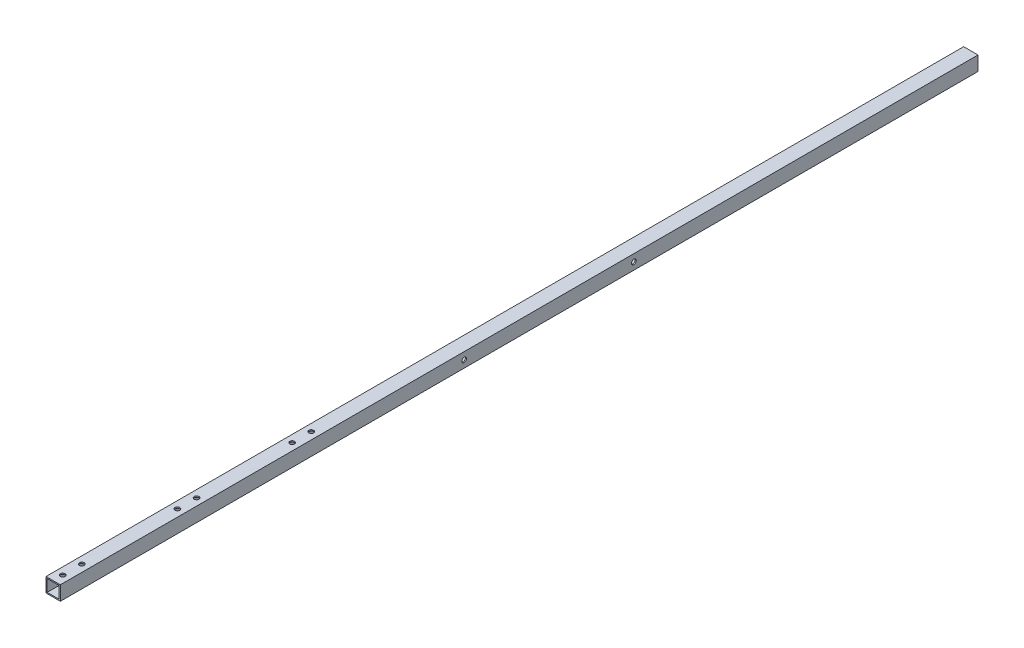
SolidWorks part; units mm, degrees
material "6061 Alloy"
ref_plane "Front Plane" through (0, 0, 0) normal (0, 0, 1) x (1, 0, 0)
ref_plane "Top Plane" through (0, 0, 0) normal (0, 1, 0) x (1, 0, 0)
ref_plane "Right Plane" through (0, 0, 0) normal (1, 0, 0) x (0, 0, -1)
sketch "Sketch1" plane through (0, 0, 0) normal (0, 0, 1) x (1, 0, 0)
  line L1 (-9.525, -9.525) -> (9.525, -9.525)
  line L2 (-9.525, -9.525) -> (-9.525, 9.525)
  line L3 (-9.525, 9.525) -> (9.525, 9.525)
  line L4 (9.525, -9.525) -> (9.525, 9.525)
  line L5 (-9.525, -9.525) -> (9.525, 9.525) construction
  line L6 (-9.525, 9.525) -> (9.525, -9.525) construction
  line L7 (-7.9375, -7.9375) -> (7.9375, -7.9375)
  line L8 (-7.9375, -7.9375) -> (-7.9375, 7.9375)
  line L9 (-7.9375, 7.9375) -> (7.9375, 7.9375)
  line L10 (7.9375, -7.9375) -> (7.9375, 7.9375)
  line L11 (-7.9375, -7.9375) -> (7.9375, 7.9375) construction
  line L12 (-7.9375, 7.9375) -> (7.9375, -7.9375) construction
  point P0 (0, 0)
  point P6 (0, 0)
  dimension "D1" = 19.05
  dimension "D2" = 19.05
  dimension "D3" = 1.5875
  dimension "D4" = 1.5875
extrude "Boss-Extrude1" add sketch "Sketch1" along normal mid plane 1219.2
sketch "Sketch2" plane through (0, 0, 0) normal (0, 1, 0) x (1, 0, 0)
  line L0 (0, -609.6) -> (0, -596.9) construction
  line L1 (9.525, -609.6) -> (-9.525, -609.6) construction
  line L2 (0, -609.6) -> (0, -571.5) construction
  circle A0 centre (0, -596.9) radius 3.175
  circle A1 centre (0, -571.5) radius 3.175
  circle A2 centre (0, -444.5) radius 3.175
  circle A3 centre (0, -419.1) radius 3.175
  circle A4 centre (0, -292.1) radius 3.175
  circle A5 centre (0, -266.7) radius 3.175
  dimension "D1" = 3
extrude "Cut-Extrude1" cut sketch "Sketch2" against normal through all both and the other way through all
sketch "Sketch3" plane through (-9.525, 0, 0) normal (-1, 0, 0) x (0, 0, 1)
  line L0 (-609.6, 0) -> (-152.4, 0) construction
  line L1 (-609.6, 9.525) -> (-609.6, -9.525) construction
  line L2 (-152.4, 0) -> (73.03, 0) construction
  circle A0 centre (-152.4, 0) radius 3.175
  circle A1 centre (73.03, 0) radius 3.175
extrude "Cut-Extrude2" cut sketch "Sketch3" against normal through all
